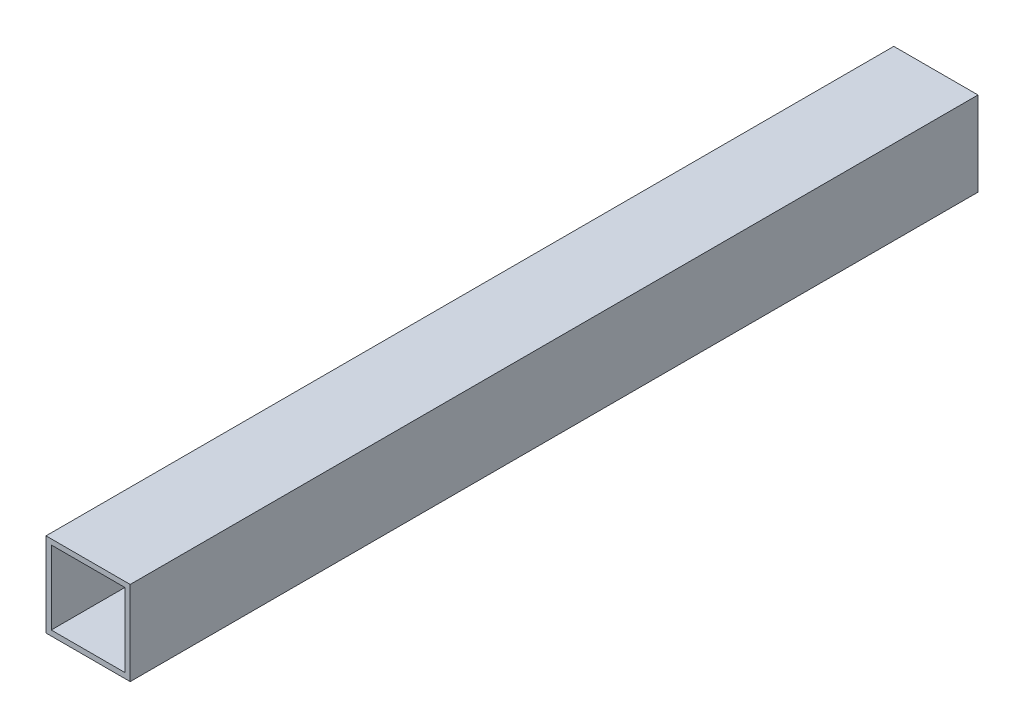
SolidWorks part; units mm, degrees
ref_plane "Front" through (0, 0, 0) normal (0, 0, 1) x (1, 0, 0)
ref_plane "Top" through (0, 0, 0) normal (0, 1, 0) x (1, 0, 0)
ref_plane "Right" through (0, 0, 0) normal (1, 0, 0) x (0, 0, -1)
sketch "Sketch1" plane through (0, 0, 0) normal (0, 0, 1) x (1, 0, 0)
  line L0 (-57.15, -3.175) -> (57.15, -3.175) construction
  line L1 (-12.7, -3.175) -> (12.7, -3.175)
  line L2 (-12.7, -3.175) -> (-12.7, -28.575)
  line L3 (-12.7, -28.575) -> (12.7, -28.575)
  line L4 (12.7, -3.175) -> (12.7, -28.575)
  line L5 (0, -28.575) -> (0, -3.175) construction
  line L6 (11.1125, -15.875) -> (-11.1125, -15.875) construction
  line L7 (-11.1125, -4.7625) -> (11.1125, -4.7625)
  line L8 (-11.1125, -4.7625) -> (-11.1125, -26.9875)
  line L9 (-11.1125, -26.9875) -> (11.1125, -26.9875)
  line L10 (11.1125, -4.7625) -> (11.1125, -26.9875)
  point P14 (0, -15.875)
  dimension "D1" = 25.4
  dimension "D3" = 1.5875
extrude "Extrude1" add sketch "Sketch1" against normal up to surface (19.05 mm away) and the other way up to surface (236.728 mm away)
